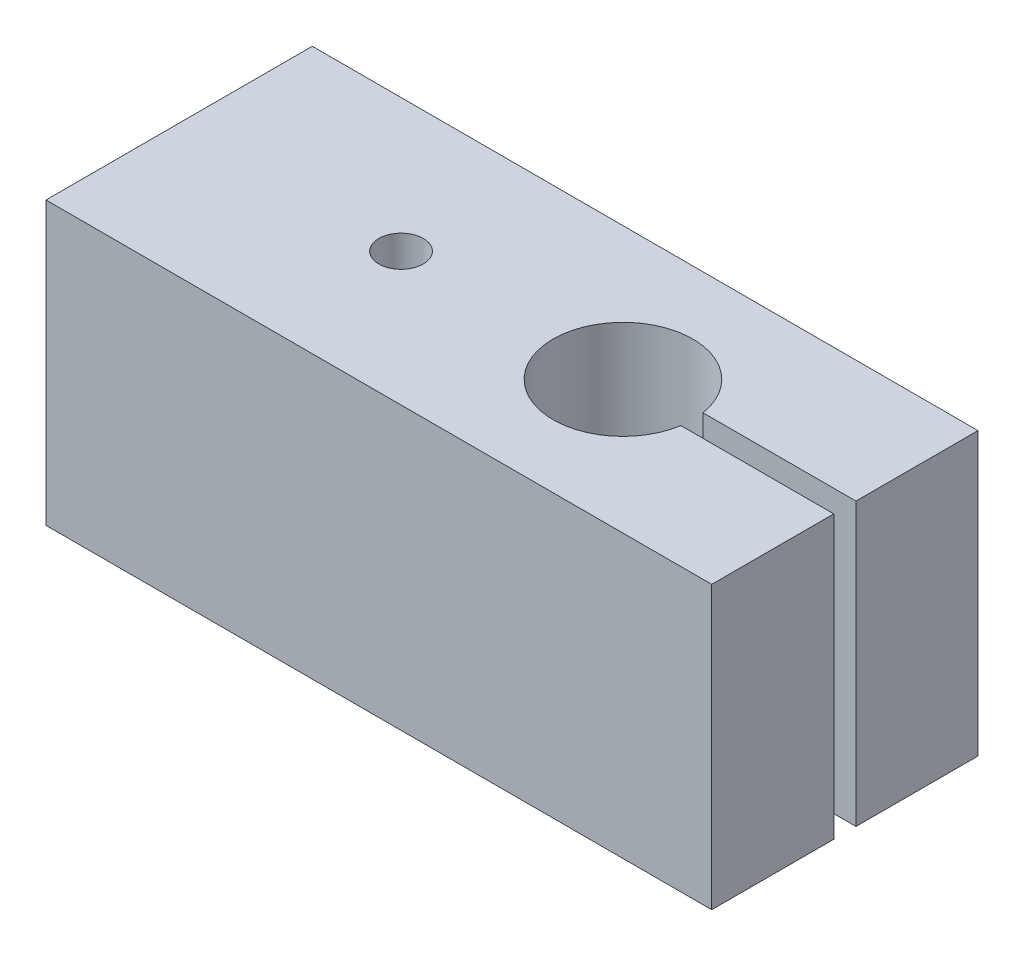
SolidWorks part; units mm, degrees
material "6061 Alloy"
ref_plane "Front Plane" through (0, 0, 0) normal (0, 0, 1) x (1, 0, 0)
ref_plane "Top Plane" through (0, 0, 0) normal (0, 1, 0) x (1, 0, 0)
ref_plane "Right Plane" through (0, 0, 0) normal (1, 0, 0) x (0, 0, -1)
sketch "Sketch1" plane through (0, 0, 0) normal (0, 1, 0) x (1, 0, 0)
  line L0 (10, -6) -> (10, 6)
  line L1 (0, 0) -> (-20, 0) construction
  line L12 (10, 6) -> (-20, 6)
  line L13 (-20, 6) -> (-20, -6)
  line L46 (-20, -6) -> (10, -6)
  circle A88 centre (0, 0) radius 3.15
  circle A89 centre (-10, 0) radius 1
  dimension "D13" = 12
  dimension "D2" = 6.3
  dimension "D3" = 2
  dimension "D4" = 10
  dimension "D5" = 20
  dimension "D6" = 10
extrude "Boss-Extrude1" add sketch "Sketch1" along normal blind 12.7
sketch "Sketch2" plane through (-20, 0, 0) normal (-1, 0, 0) x (0, 0, 1)
  line L0 (-6, 12.7) -> (6, 0) construction
  circle A0 centre (0, 6.35) radius 4
  dimension "D1" = 8
extrude "Cut-Extrude1" cut sketch "Sketch2" against normal blind 10
sketch "Sketch3" plane through (0, 12.7, 0) normal (0, 1, 0) x (1, 0, 0)
  line L0 (10, -6) -> (10, 6) construction
  line L1 (10, -0.5) -> (3.1101, -0.5)
  line L2 (10, -0.5) -> (10, 0.5)
  line L3 (10, 0.5) -> (3.1101, 0.5)
  line L4 (3.1101, -0.5) -> (3.1101, 0.5)
  circle A0 centre (0, 0) radius 3.15 construction
  dimension "D1" = 1
extrude "Cut-Extrude2" cut sketch "Sketch3" against normal through all
